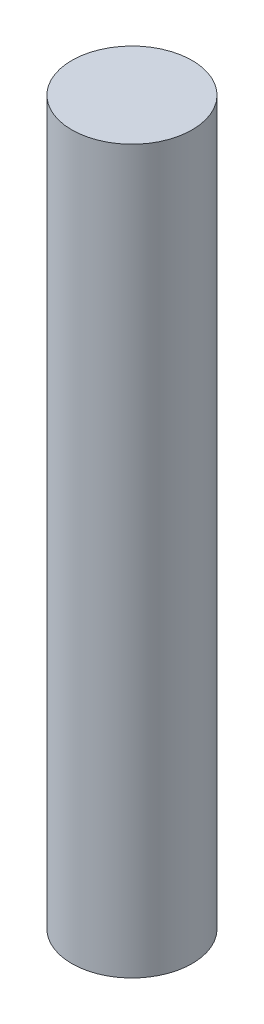
SolidWorks part; units mm, degrees
ref_plane "Front Plane" through (0, 0, 0) normal (0, 0, 1) x (1, 0, 0)
ref_plane "Top Plane" through (0, 0, 0) normal (0, 1, 0) x (1, 0, 0)
ref_plane "Right Plane" through (0, 0, 0) normal (1, 0, 0) x (0, 0, -1)
sketch "Sketch1" plane through (0, 0, 0) normal (0, 1, 0) x (1, 0, 0)
  circle A0 centre (-123.6324, -140.9655) radius 187.5
  point P3 (0, 0)
extrude "Boss-Extrude1" add sketch "Sketch1" along normal blind 2250
